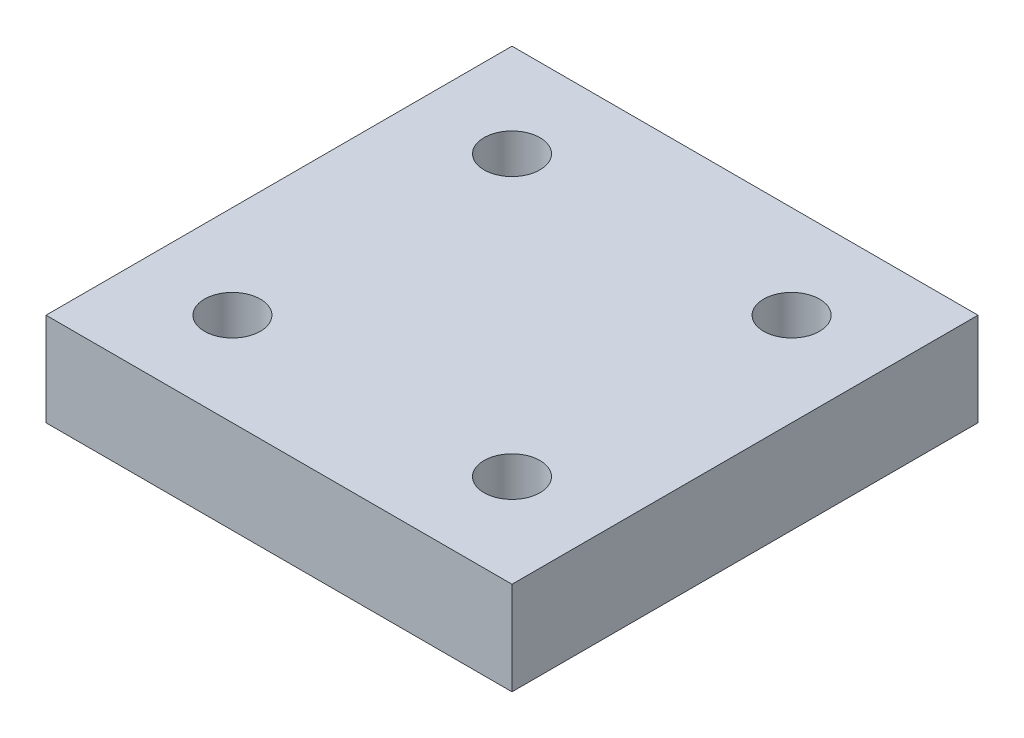
SolidWorks part; units mm, degrees
ref_plane "Front Plane" through (0, 0, 0) normal (0, 0, 1) x (1, 0, 0)
ref_plane "Top Plane" through (0, 0, 0) normal (0, 1, 0) x (1, 0, 0)
ref_plane "Right Plane" through (0, 0, 0) normal (1, 0, 0) x (0, 0, -1)
sketch "Sketch1" plane through (0, 0, 0) normal (0, 1, 0) x (1, 0, 0)
  line L1 (25, -25) -> (-25, -25)
  line L2 (25, -25) -> (25, 25)
  line L3 (25, 25) -> (-25, 25)
  line L4 (-25, -25) -> (-25, 25)
  line L5 (25, -25) -> (-25, 25) construction
  line L6 (25, 25) -> (-25, -25) construction
  line L7 (15, -15) -> (-15, -15) construction
  line L8 (15, -15) -> (15, 15) construction
  line L9 (15, 15) -> (-15, 15) construction
  line L10 (-15, -15) -> (-15, 15) construction
  line L11 (15, -15) -> (-15, 15) construction
  line L12 (15, 15) -> (-15, -15) construction
  circle A0 centre (-15, 15) radius 3
  circle A1 centre (15, 15) radius 3
  circle A2 centre (15, -15) radius 3
  circle A3 centre (-15, -15) radius 3
  point P0 (0, 0)
  point P6 (0, 0)
  dimension "D3" = 6
  dimension "D1" = 50
  dimension "D2" = 30
  dimension "D4" = 2
  dimension "D5" = 2
extrude "Boss-Extrude1" add sketch "Sketch1" along normal blind 10
